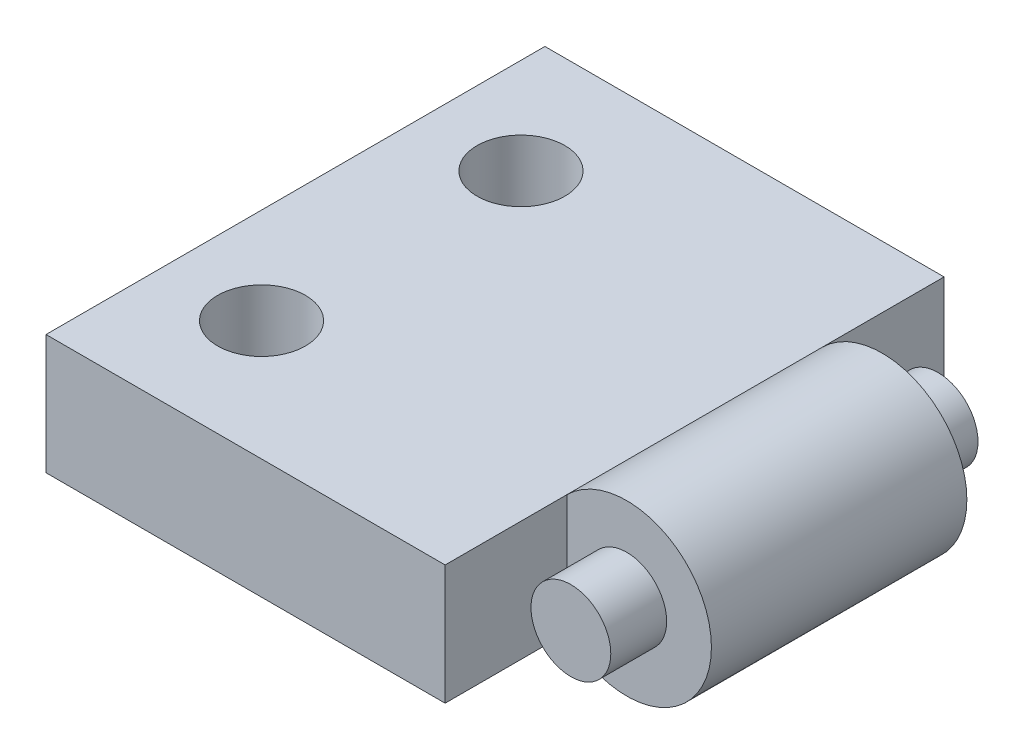
SolidWorks part; units mm, degrees
ref_plane "Front Plane" through (0, 0, 0) normal (0, 0, 1) x (1, 0, 0)
ref_plane "Top Plane" through (0, 0, 0) normal (0, 1, 0) x (1, 0, 0)
ref_plane "Right Plane" through (0, 0, 0) normal (1, 0, 0) x (0, 0, -1)
sketch "Sketch3" plane through (0, 0, 0) normal (0, 1, 0) x (1, 0, 0)
  line L0 (0, 0) -> (12.7, 0)
  line L1 (0, 0) -> (0, 15.875)
  line L2 (12.7, 0) -> (12.7, 15.875)
  line L3 (0, 15.875) -> (12.7, 15.875)
  line L4 (0, 0) -> (3.048, 0)
  line L5 (0, 15.875) -> (3.048, 15.875)
  circle A0 centre (3.048, 12.065) radius 1.397
  circle A1 centre (3.048, 3.81) radius 1.397
extrude "Boss-Extrude1" add sketch "Sketch3" along normal blind 3.81 contours L3 L1 L0 L2 A1 A0
sketch "Sketch4" plane through (0, 3.81, 0) normal (0, 1, 0) x (1, 0, 0)
  line L0 (0, 0) -> (0, 7.9375)
  line L1 (0, 0) -> (0, 15.875) construction
  line L2 (0, 7.9375) -> (12.7, 7.9375)
  line L3 (12.7, 0) -> (12.7, 15.875) construction
sketch3d "3DSketch1"
  line L0 (0, 3.81, -7.9375) -> (12.7, 3.81, -7.9375) construction
sketch "Sketch5" plane through (0, 0, -7.9375) normal (0, 0, 1) x (1, 0, 0)
  line L0 (12.7, 3.81) -> (12.7, 1.905)
  line L1 (12.7, 1.905) -> (14.605, 1.905)
  circle A0 centre (14.605, 1.905) radius 2.6941
extrude "Boss-Extrude2" add sketch "Sketch5" along normal blind 4.064 and the other way blind 4.064
sketch "Sketch6" plane through (0, 0, -3.8735) normal (0, 0, 1) x (1, 0, 0)
  circle A0 centre (14.605, 1.905) radius 2.6941
  circle A1 centre (14.605, 1.905) radius 1.27
extrude "Boss-Extrude3" add sketch "Sketch6" along normal blind 1.778 contours A1
sketch "Sketch7" plane through (0, 0, -12.0015) normal (0, 0, -1) x (-1, 0, 0)
  circle A0 centre (-14.605, 1.905) radius 2.6941
  circle A1 centre (-14.605, 1.905) radius 1.27
extrude "Boss-Extrude4" add sketch "Sketch7" along normal blind 1.778 contours A1
